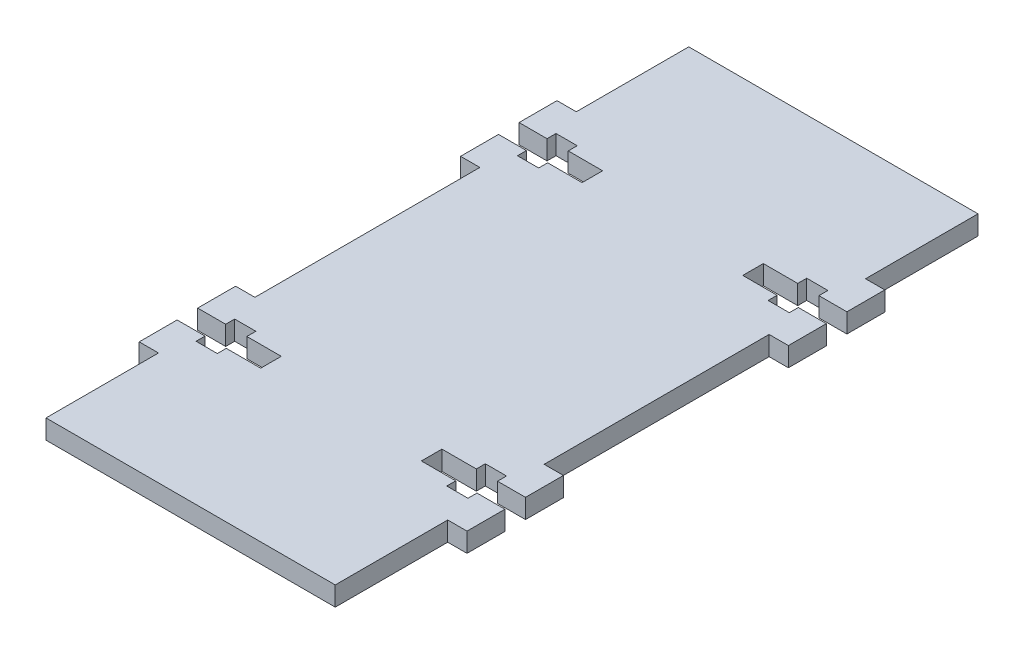
SolidWorks part; units mm, degrees
material "Thornel Mat VMA"
ref_plane "前视基准面" through (0, 0, 0) normal (0, 0, 1) x (1, 0, 0)
ref_plane "上视基准面" through (0, 0, 0) normal (0, 1, 0) x (1, 0, 0)
ref_plane "右视基准面" through (0, 0, 0) normal (1, 0, 0) x (0, 0, -1)
other "Configuration Table"
sketch "草图1" plane through (0, 0, 0) normal (0, 1, 0) x (1, 0, 0)
  line L0 (-12.4279, 0) -> (12.656, 0) construction
  line L1 (-22.5, 50) -> (22.5, 50)
  line L2 (-22.5, 50) -> (-22.5, -50)
  line L3 (-22.5, -50) -> (22.5, -50)
  line L4 (22.5, 50) -> (22.5, -50)
  line L5 (-22.5, 50) -> (22.5, -50) construction
  line L6 (-22.5, -50) -> (22.5, 50) construction
  line L7 (22.5, 32.5) -> (25.5, 32.5)
  line L8 (22.5, 32.5) -> (22.5, 17.5)
  line L9 (22.5, 17.5) -> (25.5, 17.5)
  line L10 (25.5, 32.5) -> (25.5, 17.5)
  line L11 (22.5, -17.5) -> (25.5, -17.5)
  line L12 (25.5, -32.5) -> (25.5, -17.5)
  line L13 (22.5, -32.5) -> (25.5, -32.5)
  line L14 (22.5, -32.5) -> (22.5, -17.5)
  line L15 (0, 28.5614) -> (0, -17.5) construction
  line L16 (-22.5, -32.5) -> (-22.5, -17.5)
  line L17 (-22.5, -32.5) -> (-25.5, -32.5)
  line L18 (-25.5, -32.5) -> (-25.5, -17.5)
  line L19 (-22.5, -17.5) -> (-25.5, -17.5)
  line L20 (-22.5, 17.5) -> (-25.5, 17.5)
  line L21 (-25.5, 32.5) -> (-25.5, 17.5)
  line L22 (-22.5, 32.5) -> (-25.5, 32.5)
  line L23 (-22.5, 32.5) -> (-22.5, 17.5)
  point P0 (0, 0)
  dimension "D1" = 45
  dimension "D2" = 100
  dimension "D3" = 3
  dimension "D4" = 15
  dimension "D5" = 17.5
extrude "凸台-拉伸1" add sketch "草图1" along normal mid plane 3 contours L4 L1 L2 L3 | L2 L22 L21 L20 | L2 L19 L18 L17 | L4 L13 L12 L11 | L10 L7 L4 L9
sketch "草图2" plane through (0, 1.5, 0) normal (0, 1, 0) x (1, 0, 0)
  line L0 (25.5, 32.5) -> (25.5, 17.5) construction
  line L1 (12.5, 26.6) -> (38.5, 26.6)
  line L2 (12.5, 26.6) -> (12.5, 23.4)
  line L3 (12.5, 23.4) -> (38.5, 23.4)
  line L4 (38.5, 26.6) -> (38.5, 23.4)
  line L5 (12.5, 26.6) -> (38.5, 23.4) construction
  line L6 (12.5, 23.4) -> (38.5, 26.6) construction
  line L7 (25.5, 25) -> (19.5, 25) construction
  line L9 (17.85, 28) -> (21.15, 28)
  line L10 (17.85, 28) -> (17.85, 22)
  line L11 (17.85, 22) -> (21.15, 22)
  line L12 (21.15, 28) -> (21.15, 22)
  line L13 (17.85, 28) -> (21.15, 22) construction
  line L14 (17.85, 22) -> (21.15, 28) construction
  point P0 (25.5, 25)
  line M26 (25.5, 17.5) -> (25.5, 32.5)
  dimension "D1" = 3.2
  dimension "D2" = 26
  dimension "D3" = 6
  dimension "D4" = 3.3
  dimension "D5" = 6
extrude "切除-拉伸1" cut sketch "草图2" against normal through all both and the other way through all contours L10 L1 L2 L3 | L12 L9 L10 L1 | L12 L1 L10 L3 | L12 L3 L10 L11 | L1 L12 L3 M26
mirror "镜向1" about plane through (0, 0, 0) normal (1, 0, 0) of "切除-拉伸1"
mirror "镜向2" about plane through (0, 0, 0) normal (0, 0, 1) of "镜向1", "切除-拉伸1"
